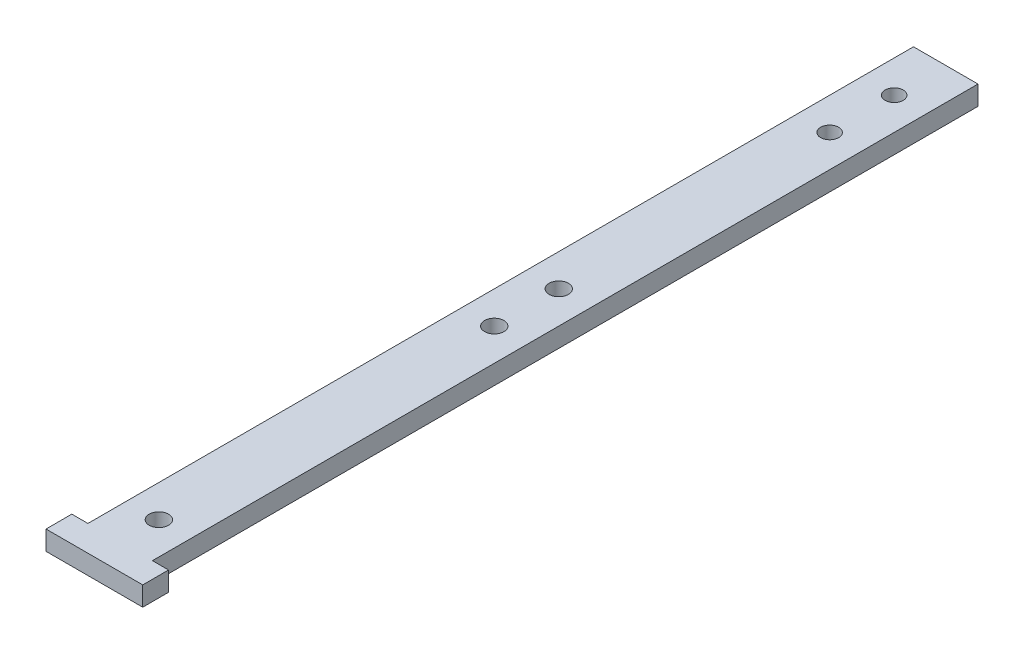
SolidWorks part; units mm, degrees
material "1060 Alloy"
ref_plane "Front Plane" through (0, 0, 0) normal (0, 0, 1) x (1, 0, 0)
ref_plane "Top Plane" through (0, 0, 0) normal (0, 1, 0) x (1, 0, 0)
ref_plane "Right Plane" through (0, 0, 0) normal (1, 0, 0) x (0, 0, -1)
sketch "Sketch1" plane through (0, 0, 0) normal (0, 1, 0) x (1, 0, 0)
  line L1 (34.8767, -142.9893) -> (49.8767, -142.9893)
  line L2 (34.8767, -142.9893) -> (34.8767, -146.9893)
  line L3 (34.8767, -146.9893) -> (49.8767, -146.9893)
  line L4 (49.8767, -142.9893) -> (49.8767, -146.9893)
  line L6 (37.3767, -14.9893) -> (47.3767, -14.9893)
  line L7 (37.3767, -14.9893) -> (37.3767, -142.9893)
  line L8 (37.3767, -142.9893) -> (47.3767, -142.9893)
  line L9 (47.3767, -14.9893) -> (47.3767, -142.9893)
  circle A0 centre (42.3767, -22.9893) radius 1.4
  circle A1 centre (42.3767, -32.9893) radius 1.4
  circle A4 centre (42.3767, -136.9893) radius 1.5
  circle A5 centre (42.3767, -84.9893) radius 1.5
  circle A6 centre (42.3767, -74.9893) radius 1.5
  point P10 (42.3767, -142.9893)
  point P11 (42.3767, -142.9893)
  point P24 (42.3767, -146.9893)
  dimension "D6" = 3
  dimension "D12" = 10
  dimension "D13" = 3
  dimension "D7" = 58
  dimension "D10" = 5
  dimension "D15" = 3
  dimension "D16" = 5
  dimension "D17" = 10
  dimension "D18" = 5
  dimension "D19" = 5
  dimension "D1" = 128
  dimension "D2" = 4
  dimension "D3" = 15
  dimension "D4" = 10
  dimension "D5" = 2.5
  dimension "D8" = 8
  dimension "D9" = 10
  dimension "D11" = 2.5
extrude "Boss-Extrude1" add sketch "Sketch1" along normal blind 3 contours L9 L6 L7 L1 | L4 L1 L2 L3
